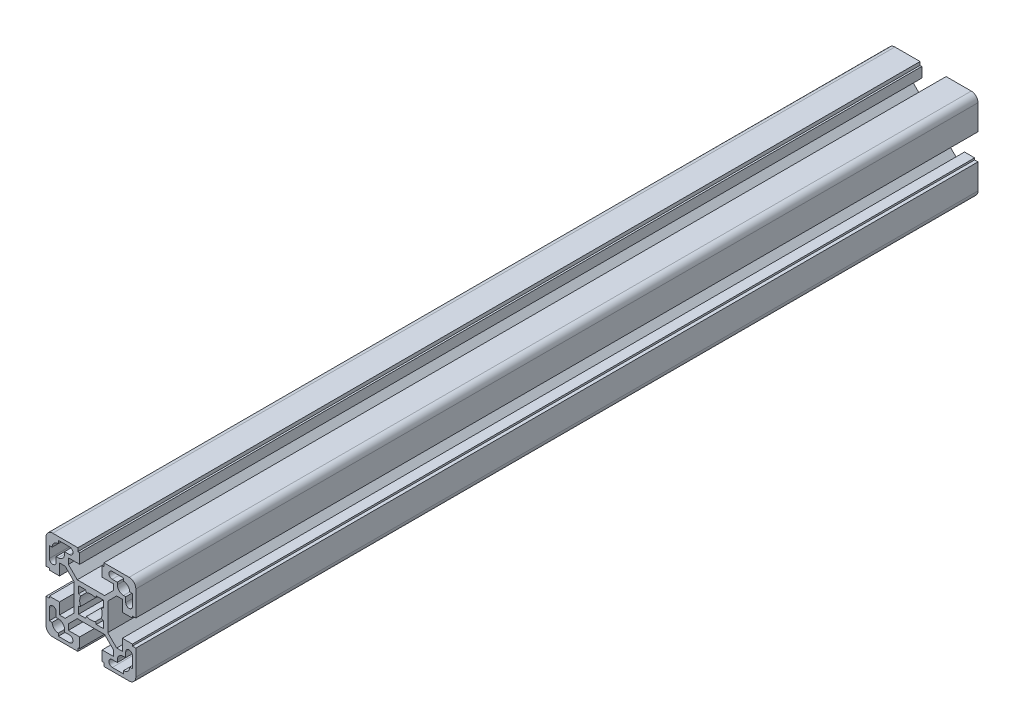
SolidWorks part; units mm, degrees
material "6061 Alloy"
ref_plane "Front Plane" through (0, 0, 0) normal (0, 0, 1) x (1, 0, 0)
ref_plane "Top Plane" through (0, 0, 0) normal (0, 1, 0) x (1, 0, 0)
ref_plane "Right Plane" through (0, 0, 0) normal (1, 0, 0) x (0, 0, -1)
sketch "Sketch1" plane through (0, 0, 0) normal (0, 0, 1) x (1, 0, 0)
  line L0 (5.8, -20) -> (17, -20)
  line L1 (14, -10.05) -> (11.4642, -10.05)
  line L2 (0, -21.1722) -> (0, 18.817) construction
  line L3 (0, 21.1722) -> (0, -18.817) construction
  line L4 (14.5, -18.5) -> (9.5, -18.5)
  line L5 (18.5, 5) -> (14, 5)
  line L6 (6.0858, -7.5) -> (10.05, -11.4642)
  line L7 (20, 5.8) -> (18.5, 5.8)
  line L8 (14, 5) -> (14, 10.05)
  line L9 (18.5, 5.8) -> (18.5, 5)
  line L10 (18.5, 14.5) -> (17.25, 14.5)
  line L11 (14.5, 11.75) -> (15.5, 11.75)
  line L12 (14.5, 17.25) -> (14.5, 18.5)
  line L13 (18.5, 9.5) -> (18.5, 14.5)
  line L14 (15.5, 11.75) -> (15.5, 9.5)
  line L15 (20, 17) -> (20, 5.8)
  line L16 (5.5, 5.5) -> (2.3979, 5.5)
  line L17 (2.3979, 5.5) -> (1.9983, 4.5833)
  line L18 (5.5, 2.3979) -> (5.5, 5.5)
  line L19 (4.5833, 1.9983) -> (5.5, 2.3979)
  line L20 (5, -14) -> (5, -18.5)
  line L21 (11.4642, 10.05) -> (7.5, 6.0858)
  line L22 (-6.0858, 7.5) -> (6.0858, 7.5)
  line L23 (11.75, 15.5) -> (11.75, 14.5)
  line L24 (5, -18.5) -> (5.8, -18.5)
  line L25 (5.8, -18.5) -> (5.8, -20)
  line L26 (10.05, -11.4642) -> (10.05, -14)
  line L27 (10.05, -14) -> (5, -14)
  line L28 (9.5, -15.5) -> (11.75, -15.5)
  line L29 (11.75, -15.5) -> (11.75, -14.5)
  line L30 (9.5, 15.5) -> (11.75, 15.5)
  line L31 (10.05, 14) -> (5, 14)
  line L32 (10.05, 11.4642) -> (10.05, 14)
  line L33 (5.8, 18.5) -> (5.8, 20)
  line L34 (5, 18.5) -> (5.8, 18.5)
  line L35 (7.5, -6.0858) -> (7.5, 6.0858)
  line L36 (5, 14) -> (5, 18.5)
  line L37 (6.0858, 7.5) -> (10.05, 11.4642)
  line L38 (14.5, 18.5) -> (9.5, 18.5)
  line L39 (14, 10.05) -> (11.4642, 10.05)
  line L40 (5.8, 20) -> (17, 20)
  line L41 (-18.5, -5) -> (-14, -5)
  line L42 (-6.0858, -7.5) -> (6.0858, -7.5)
  line L43 (11.4642, -10.05) -> (7.5, -6.0858)
  line L44 (-20, -5.8) -> (-18.5, -5.8)
  line L45 (-14, -5) -> (-14, -10.05)
  line L46 (-18.5, -5.8) -> (-18.5, -5)
  line L47 (-18.5, -14.5) -> (-17.25, -14.5)
  line L48 (4.5833, -1.9983) -> (5.5, -2.3979)
  line L49 (5.5, -2.3979) -> (5.5, -5.5)
  line L50 (2.3979, -5.5) -> (1.9983, -4.5833)
  line L51 (5.5, -5.5) -> (2.3979, -5.5)
  line L52 (-14.5, -11.75) -> (-15.5, -11.75)
  line L53 (-14.5, -17.25) -> (-14.5, -18.5)
  line L54 (-18.5, -9.5) -> (-18.5, -14.5)
  line L55 (-15.5, -11.75) -> (-15.5, -9.5)
  line L56 (-20, -17) -> (-20, -5.8)
  line L57 (-5.5, -5.5) -> (-2.3979, -5.5)
  line L58 (-2.3979, -5.5) -> (-1.9983, -4.5833)
  line L59 (-5.5, -2.3979) -> (-5.5, -5.5)
  line L60 (-4.5833, -1.9983) -> (-5.5, -2.3979)
  line L61 (-11.4642, -10.05) -> (-7.5, -6.0858)
  line L62 (-5.8, 20) -> (-17, 20)
  line L63 (-14, 10.05) -> (-11.4642, 10.05)
  line L64 (-14.5, 18.5) -> (-9.5, 18.5)
  line L65 (-6.0858, 7.5) -> (-10.05, 11.4642)
  line L66 (-5, 14) -> (-5, 18.5)
  line L67 (-7.5, -6.0858) -> (-7.5, 6.0858)
  line L68 (-5, 18.5) -> (-5.8, 18.5)
  line L69 (-5.8, 18.5) -> (-5.8, 20)
  line L70 (-10.05, 11.4642) -> (-10.05, 14)
  line L71 (-10.05, 14) -> (-5, 14)
  line L72 (-9.5, 15.5) -> (-11.75, 15.5)
  line L73 (-11.75, -15.5) -> (-11.75, -14.5)
  line L74 (-9.5, -15.5) -> (-11.75, -15.5)
  line L75 (-10.05, -14) -> (-5, -14)
  line L76 (-10.05, -11.4642) -> (-10.05, -14)
  line L77 (-5.8, -18.5) -> (-5.8, -20)
  line L78 (-5, -18.5) -> (-5.8, -18.5)
  line L79 (-11.75, 15.5) -> (-11.75, 14.5)
  line L80 (-11.4642, 10.05) -> (-7.5, 6.0858)
  line L81 (-5, -14) -> (-5, -18.5)
  line L82 (-4.5833, 1.9983) -> (-5.5, 2.3979)
  line L83 (-5.5, 2.3979) -> (-5.5, 5.5)
  line L84 (-2.3979, 5.5) -> (-1.9983, 4.5833)
  line L85 (-5.5, 5.5) -> (-2.3979, 5.5)
  line L86 (-20, 17) -> (-20, 5.8)
  line L87 (-15.5, 11.75) -> (-15.5, 9.5)
  line L88 (20, -17) -> (20, -5.8)
  line L89 (15.5, -11.75) -> (15.5, -9.5)
  line L90 (18.5, -9.5) -> (18.5, -14.5)
  line L91 (14.5, -17.25) -> (14.5, -18.5)
  line L92 (14.5, -11.75) -> (15.5, -11.75)
  line L93 (18.5, -14.5) -> (17.25, -14.5)
  line L94 (-18.5, 9.5) -> (-18.5, 14.5)
  line L95 (-14.5, 17.25) -> (-14.5, 18.5)
  line L96 (18.5, -5.8) -> (18.5, -5)
  line L97 (14, -5) -> (14, -10.05)
  line L98 (20, -5.8) -> (18.5, -5.8)
  line L99 (18.5, -5) -> (14, -5)
  line L100 (-14.5, 11.75) -> (-15.5, 11.75)
  line L101 (-18.5, 14.5) -> (-17.25, 14.5)
  line L102 (-18.5, 5.8) -> (-18.5, 5)
  line L103 (-14, 5) -> (-14, 10.05)
  line L104 (-20, 5.8) -> (-18.5, 5.8)
  line L105 (-6.0858, -7.5) -> (-10.05, -11.4642)
  line L106 (-18.5, 5) -> (-14, 5)
  line L107 (-14.5, -18.5) -> (-9.5, -18.5)
  line L108 (-20, 0) -> (20.788, 0) construction
  line L109 (-14, -10.05) -> (-11.4642, -10.05)
  line L110 (-5.8, -20) -> (-17, -20)
  arc A0 (14.5, -11.75) -> (11.75, -14.5) centre (14.5, -14.5) ccw
  arc A1 (18.5, 9.5) -> (15.5, 9.5) centre (17, 9.5) cw
  arc A2 (14.5, 17.25) -> (17.25, 14.5) centre (14.5, 14.5) cw
  arc A3 (17, 20) -> (20, 17) centre (17, 17) cw
  arc A4 (-1.9983, 4.5833) -> (1.9983, 4.5833) centre (0, 0) cw
  arc A5 (9.5, 15.5) -> (9.5, 18.5) centre (9.5, 17) cw
  arc A6 (9.5, -15.5) -> (9.5, -18.5) centre (9.5, -17) ccw
  arc A7 (14.5, 11.75) -> (11.75, 14.5) centre (14.5, 14.5) cw
  arc A8 (4.5833, -1.9983) -> (4.5833, 1.9983) centre (0, 0) ccw
  arc A9 (-18.5, -9.5) -> (-15.5, -9.5) centre (-17, -9.5) cw
  arc A10 (-14.5, -17.25) -> (-17.25, -14.5) centre (-14.5, -14.5) cw
  arc A11 (-1.9983, -4.5833) -> (1.9983, -4.5833) centre (0, 0) ccw
  arc A12 (-17, -20) -> (-20, -17) centre (-17, -17) cw
  arc A13 (-4.5833, -1.9983) -> (-4.5833, 1.9983) centre (0, 0) cw
  arc A14 (-14.5, 11.75) -> (-11.75, 14.5) centre (-14.5, 14.5) ccw
  arc A15 (-9.5, -15.5) -> (-9.5, -18.5) centre (-9.5, -17) cw
  arc A16 (-9.5, 15.5) -> (-9.5, 18.5) centre (-9.5, 17) ccw
  arc A17 (-17, 20) -> (-20, 17) centre (-17, 17) ccw
  arc A18 (17, -20) -> (20, -17) centre (17, -17) ccw
  arc A19 (14.5, -17.25) -> (17.25, -14.5) centre (14.5, -14.5) ccw
  arc A20 (18.5, -9.5) -> (15.5, -9.5) centre (17, -9.5) ccw
  arc A21 (-14.5, 17.25) -> (-17.25, 14.5) centre (-14.5, 14.5) ccw
  arc A22 (-18.5, 9.5) -> (-15.5, 9.5) centre (-17, 9.5) ccw
  arc A23 (-14.5, -11.75) -> (-11.75, -14.5) centre (-14.5, -14.5) cw
  point P55 (7.5, 0)
  point P101 (-7.5, 0)
  point P116 (0, -7.5)
  point P149 (0, 7.5)
extrude "Extrude1" add sketch "Sketch1" along normal blind 375
hole_wizard "M12 Tapped Hole1" [suppressed] positions "3DSketch2" profile "Sketch3" tap size "M12" standard "ISO"
sketch3d "3DSketch2"
  line L0 (-20, 17, 0) -> (-20, 5.8, 0) construction
  line L1 (-5.8, 20, 0) -> (-17, 20, 0) construction
  line L2 (-5.8, 20, 200) -> (-17, 20, 200) construction
  line L3 (-20, 17, 200) -> (-20, 5.8, 200) construction
  point P0 (0, 0, 200)
  point P2 (0, 0, 0)
  dimension "D1" = 20
  dimension "D2" = 20
  dimension "D3" = 20
  dimension "D4" = 20
sketch "Sketch3" plane through (0, 0, 200) normal (1, 0, 0) x (0, -1, 0)
  line L0 (0, 0) -> (0, 35.8144)
  line L1 (0, 35.8144) -> (5.1, 32.75)
  line L2 (5.1, 32.75) -> (5.1, 0.925)
  line L3 (5.1, 0.925) -> (6.025, 0)
  line L5 (6.025, 0) -> (0, 0)
  line L6 (-5.1, 0.925) -> (-6.025, 0) construction
  line L10 (0, 35.8144) -> (-5.1, 32.75) construction
  line L11 (0, -6.35) -> (0, 107.95) construction
  dimension "Tap Drill Dia." = 10.2
  dimension "Tap Drill Depth" = 32.75
  dimension "Near C'Sink Dia." = 12.05
  dimension "Near C'Sink Angle" = 90
  dimension "Drill Angle" = 118
cosmetic thread "Hole Thread1" [suppressed] parameters "D1"=24, "D2"=12
cosmetic thread "Hole Thread2" [suppressed] parameters "D1"=24, "D2"=12
hole_wizard "Ø9.8 (9.8) Diameter Hole1" [suppressed] positions "3DSketch3" profile "Sketch4" hole size "Ø9.8" standard "ISO"
sketch3d "3DSketch3"
  line L0 (-5.8, 20, 200) -> (-17, 20, 200) construction
  line L1 (20, -17, 200) -> (20, -5.8, 200) construction
  line L2 (17, 20, 0) -> (5.8, 20, 0) construction
  line L3 (20, -17, 0) -> (20, -5.8, 0) construction
  point P0 (0, 20, 184)
  point P2 (20, 0, 184)
  point P4 (0, 20, 16)
  point P6 (20, 0, 16)
  dimension "D1" = 16
  dimension "D2" = 20
  dimension "D3" = 20
  dimension "D4" = 16
  dimension "D5" = 16
  dimension "D6" = 16
sketch "Sketch4" plane through (0, 20, 184) normal (1, 0, 0) x (0, 0, 1)
  line L0 (0, 0) -> (0, 40)
  line L1 (0, 40) -> (4.9, 40)
  line L2 (4.9, 40) -> (4.9, 0)
  line L5 (4.9, 0) -> (0, 0)
  line L11 (0, -6.35) -> (0, 107.95) construction
  dimension "Thru Hole Dia." = 9.8
  dimension "Thru Hole Depth" = 40
hole_wizard "Ø17.0 (17) Diameter Hole1" [suppressed] positions "3DSketch4" profile "Sketch5" hole size "Ø17.0" standard "ISO"
sketch3d "3DSketch4"
  line L0 (-5.8, 20, 200) -> (-17, 20, 200) construction
  line L1 (-5.8, 20, 0) -> (-17, 20, 0) construction
  point P0 (0, 20, 177.5)
  point P2 (0, 20, 22.5)
  dimension "D1" = 20
  dimension "D2" = 22.5
  dimension "D3" = 22.5
sketch "Sketch5" plane through (0, 20, 177.5) normal (1, 0, 0) x (0, 0, 1)
  line L0 (0, 0) -> (0, 40)
  line L1 (0, 40) -> (8.5, 40)
  line L2 (8.5, 40) -> (8.5, 0)
  line L5 (8.5, 0) -> (0, 0)
  line L11 (0, -6.35) -> (0, 107.95) construction
  dimension "Thru Hole Dia." = 17
  dimension "Thru Hole Depth" = 40
